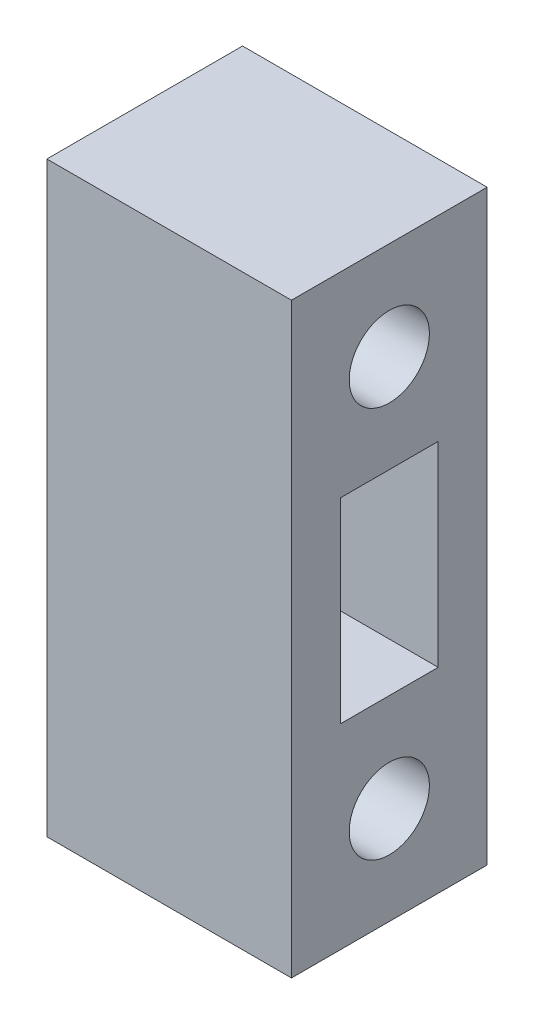
SolidWorks part; units mm, degrees
ref_plane "Front Plane" through (0, 0, 0) normal (0, 0, 1) x (1, 0, 0)
ref_plane "Top Plane" through (0, 0, 0) normal (0, 1, 0) x (1, 0, 0)
ref_plane "Right Plane" through (0, 0, 0) normal (1, 0, 0) x (0, 0, -1)
sketch "Sketch1" plane through (0, 0, 0) normal (1, 0, 0) x (0, 0, -1)
  line L0 (0, 20) -> (0, -20) construction
  line L2 (-10, -30) -> (10, -30)
  line L3 (-10, -30) -> (-10, 30)
  line L4 (-10, 30) -> (10, 30)
  line L5 (10, -30) -> (10, 30)
  line L6 (-10, -30) -> (10, 30) construction
  line L7 (-10, 30) -> (10, -30) construction
  line L8 (-5, -10) -> (5, -10)
  line L9 (-5, -10) -> (-5, 10)
  line L10 (-5, 10) -> (5, 10)
  line L11 (5, -10) -> (5, 10)
  line L12 (-5, -10) -> (5, 10) construction
  line L13 (-5, 10) -> (5, -10) construction
  circle A0 centre (0, 20) radius 4.1
  circle A1 centre (0, -20) radius 4.1
  point P5 (0, 0)
  point P10 (0, 0)
  dimension "D1" = 40
  dimension "D2" = 8.2
  dimension "D3" = 20
  dimension "D4" = 60
  dimension "D5" = 20
  dimension "D6" = 10
extrude "Boss-Extrude1" add sketch "Sketch1" along normal blind 25
